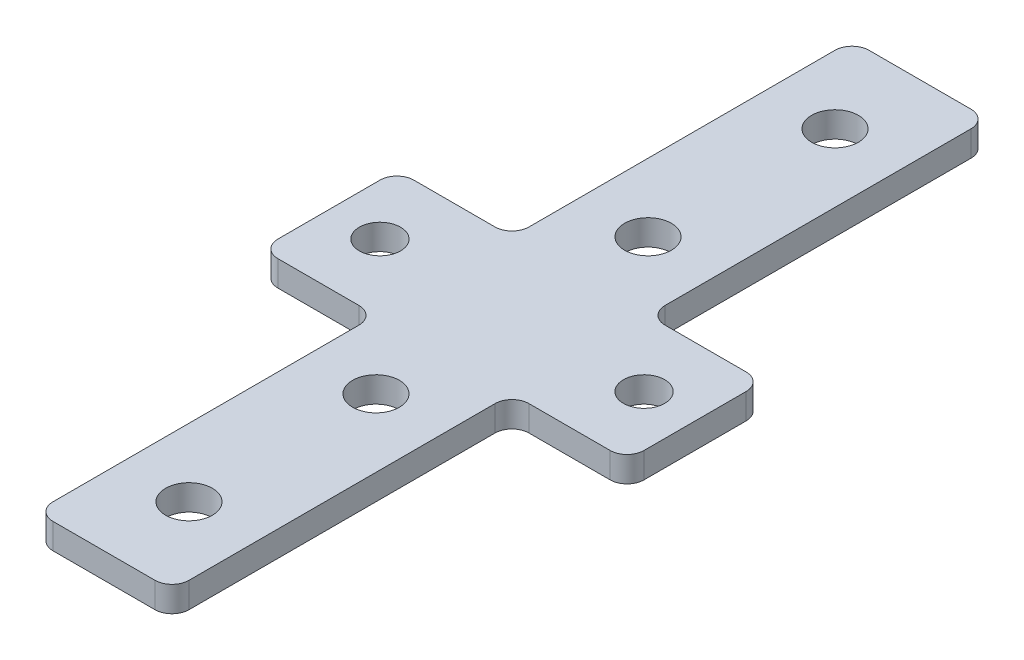
SolidWorks part; units mm, degrees
ref_plane "前视基准面" through (0, 0, 0) normal (0, 0, 1) x (1, 0, 0)
ref_plane "上视基准面" through (0, 0, 0) normal (0, 1, 0) x (1, 0, 0)
ref_plane "右视基准面" through (0, 0, 0) normal (1, 0, 0) x (0, 0, -1)
other "Configuration Table"
sketch "草图1" plane through (0, 0, 0) normal (0, 1, 0) x (1, 0, 0)
  line L0 (-1000, 0) -> (49000, 0) construction
  line L1 (-6, 48) -> (6, 48)
  line L3 (-6, -48) -> (6, -48)
  line L5 (-8, 48) -> (8, -48) construction
  line L6 (-8, -48) -> (8, 48) construction
  line L8 (-21.5383, -6) -> (-21.5383, 6)
  line L10 (21.5383, -6) -> (21.5383, 6)
  line L11 (-21.5383, -8) -> (21.5383, 8) construction
  line L12 (-21.5383, 8) -> (21.5383, -8) construction
  line L13 (0, -1000) -> (0, 49000) construction
  line L14 (-8, 46) -> (-8, 10)
  line L15 (-8, -46) -> (-8, -10)
  line L16 (8, -46) -> (8, -10)
  line L17 (8, 46) -> (8, 10)
  line L18 (-19.5383, 8) -> (-10, 8)
  line L19 (-19.5383, -8) -> (-10, -8)
  line L20 (10, -8) -> (19.5383, -8)
  line L21 (19.5383, 8) -> (10, 8)
  circle A0 centre (0, 38) radius 2.75
  circle A1 centre (0, 16) radius 2.75
  circle A2 centre (0, -16) radius 2.75
  circle A3 centre (0, -38) radius 2.75
  circle A4 centre (-15.5383, 0) radius 2.4233
  circle A5 centre (15.5383, 0) radius 2.4233
  arc A6 (10, -8) -> (8, -10) centre (10, -10) ccw
  arc A7 (6, -48) -> (8, -46) centre (6, -46) ccw
  arc A8 (-6, -48) -> (-8, -46) centre (-6, -46) cw
  arc A9 (-21.5383, 6) -> (-19.5383, 8) centre (-19.5383, 6) cw
  arc A10 (-19.5383, -8) -> (-21.5383, -6) centre (-19.5383, -6) cw
  arc A11 (-8, -10) -> (-10, -8) centre (-10, -10) ccw
  arc A12 (19.5383, -8) -> (21.5383, -6) centre (19.5383, -6) ccw
  arc A13 (21.5383, 6) -> (19.5383, 8) centre (19.5383, 6) ccw
  arc A14 (10, 8) -> (8, 10) centre (10, 10) cw
  arc A15 (6, 48) -> (8, 46) centre (6, 46) cw
  arc A16 (-8, 46) -> (-6, 48) centre (-6, 46) cw
  arc A17 (-8, 10) -> (-10, 8) centre (-10, 10) cw
  point P0 (0, 0)
  point P6 (0, 0)
  point P33 (8, -8)
  point P64 (-8, 8)
  dimension "D4" = 5.5
  dimension "D6" = 5.5
  dimension "D9" = 2
  dimension "D1" = 96
  dimension "D2" = 16
  dimension "D3" = 16
  dimension "D5" = 10
  dimension "D7" = 22
  dimension "D8" = 6
extrude "凸台-拉伸1" add sketch "草图1" along normal blind 3
